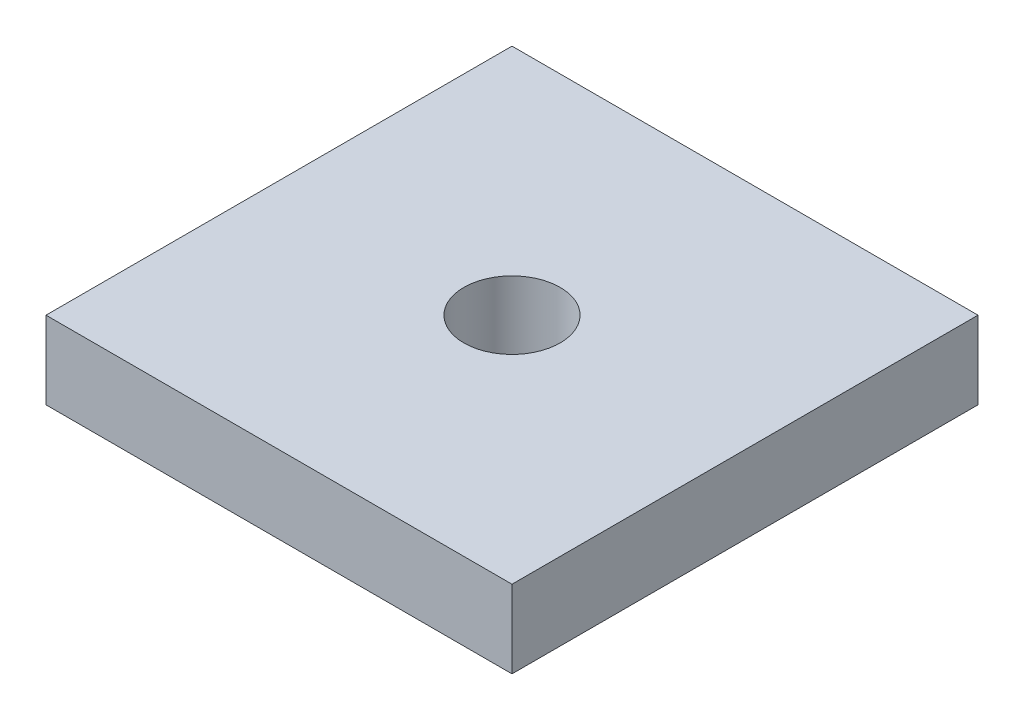
SolidWorks part; units mm, degrees
ref_plane "Front Plane" through (0, 0, 0) normal (0, 0, 1) x (1, 0, 0)
ref_plane "Top Plane" through (0, 0, 0) normal (0, 1, 0) x (1, 0, 0)
ref_plane "Right Plane" through (0, 0, 0) normal (1, 0, 0) x (0, 0, -1)
sketch "Sketch1" plane through (0, 0, 0) normal (0, 1, 0) x (1, 0, 0)
  line L1 (-15, -15) -> (15, -15)
  line L2 (-15, -15) -> (-15, 15)
  line L3 (-15, 15) -> (15, 15)
  line L4 (15, -15) -> (15, 15)
  line L5 (-15, -15) -> (15, 15) construction
  line L6 (-15, 15) -> (15, -15) construction
  circle A0 centre (0, 0) radius 3.1
  point P0 (0, 0)
  dimension "D3" = 6.2
  dimension "D1" = 30
  dimension "D2" = 30
extrude "Boss-Extrude1" add sketch "Sketch1" along normal blind 5
